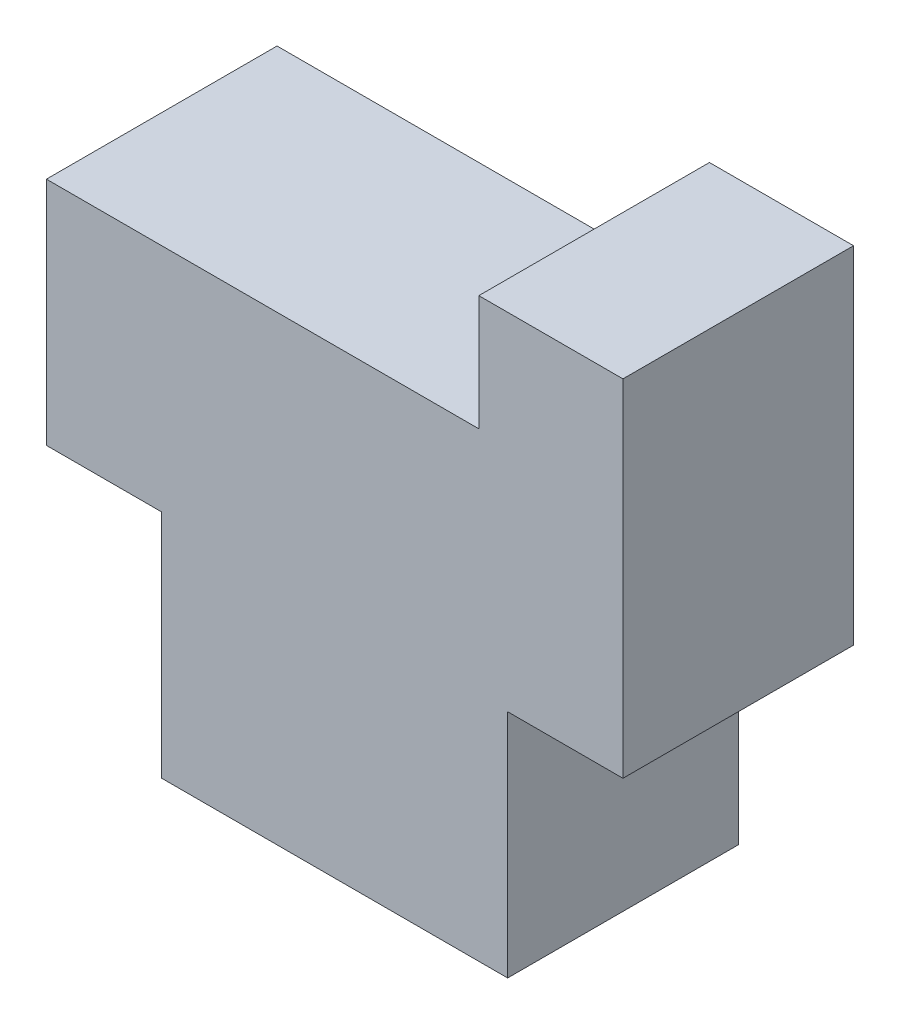
SolidWorks part; units mm, degrees
ref_plane "Front Plane" through (0, 0, 0) normal (0, 0, 1) x (1, 0, 0)
ref_plane "Top Plane" through (0, 0, 0) normal (0, 1, 0) x (1, 0, 0)
ref_plane "Right Plane" through (0, 0, 0) normal (1, 0, 0) x (0, 0, -1)
sketch "Sketch1" plane through (0, 0, 0) normal (0, 0, 1) x (1, 0, 0)
  line L0 (0, 0) -> (6, 0)
  line L1 (0, 0) -> (0, 4)
  line L2 (6, 0) -> (6, 4)
  line L3 (6, 4) -> (8, 4)
  line L4 (-2, 8) -> (5.5, 8)
  line L5 (5.5, 8) -> (5.5, 10)
  line L6 (5.5, 10) -> (8, 10)
  line L7 (8, 10) -> (8, 4)
  line L8 (0, 4) -> (-2, 4)
  line L9 (-2, 4) -> (-2, 8)
  dimension "D1" = 6
  dimension "D2" = 4
  dimension "D3" = 2
  dimension "D4" = 2
  dimension "D5" = 4
  dimension "D6" = 7.5
  dimension "D7" = 2
extrude "Boss-Extrude1" add sketch "Sketch1" along normal blind 4
